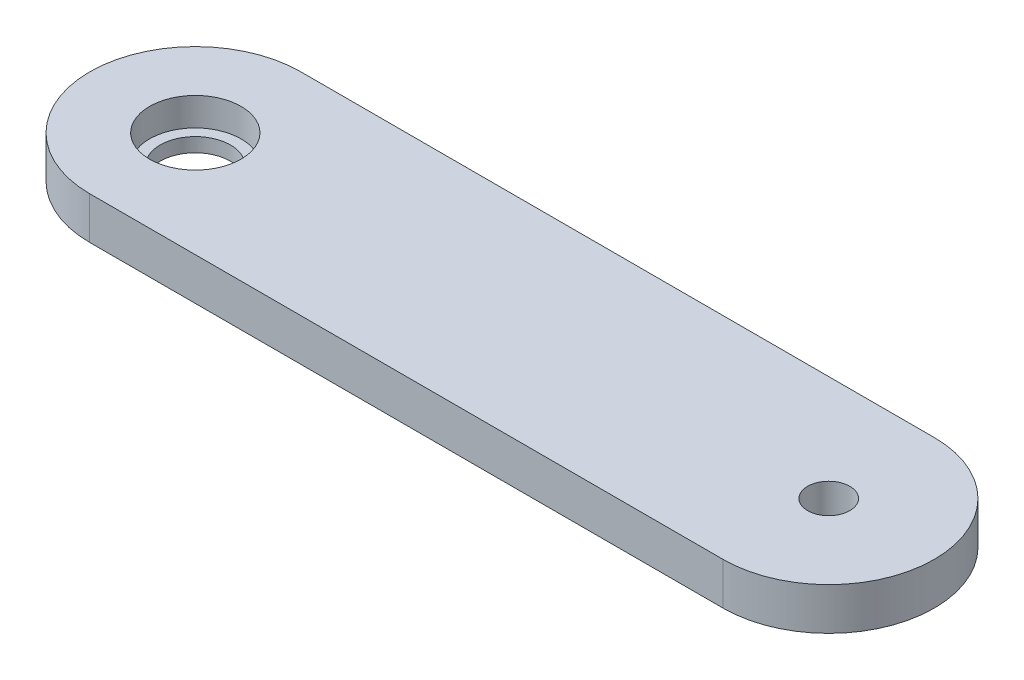
SolidWorks part; units mm, degrees
ref_plane "Front Plane" through (0, 0, 0) normal (0, 0, 1) x (1, 0, 0)
ref_plane "Top Plane" through (0, 0, 0) normal (0, 1, 0) x (1, 0, 0)
ref_plane "Right Plane" through (0, 0, 0) normal (1, 0, 0) x (0, 0, -1)
sketch "Sketch2" plane through (0, 0, 0) normal (0, 1, 0) x (1, 0, 0)
  line L1 (-45, 15) -> (45, 15)
  line L3 (-45, -15) -> (45, -15)
  arc A0 (-45, 15) -> (-45, -15) centre (-45, 0) ccw
  arc A1 (45, -15) -> (45, 15) centre (45, 0) ccw
  circle A2 centre (-45, 0) radius 5
  circle A3 centre (45, 0) radius 3
  point P0 (0, 0)
extrude "Boss-Extrude1" add sketch "Sketch2" along normal blind 6
sketch "Sketch3" plane through (0, 6, 0) normal (0, 1, 0) x (1, 0, 0)
  circle A0 centre (-45, 0) radius 6.5
extrude "Cut-Extrude1" cut sketch "Sketch3" against normal blind 4
